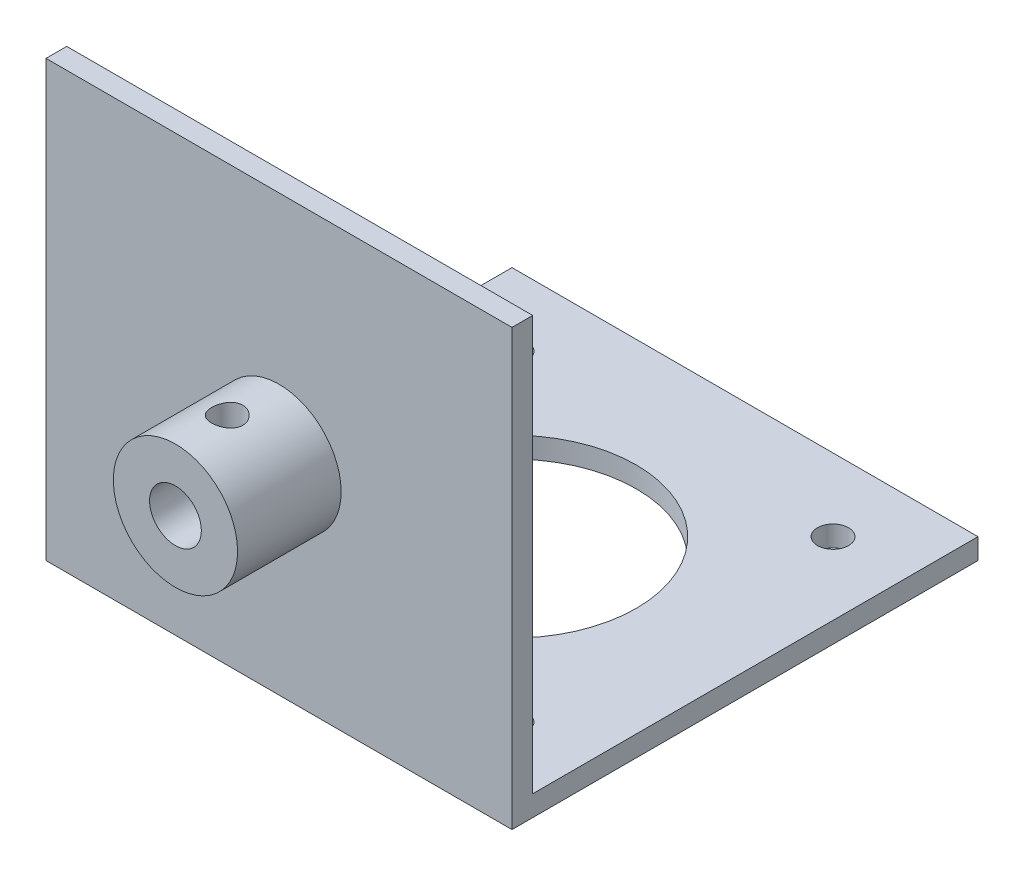
SolidWorks part; units mm, degrees
material "5052-H36"
ref_plane "前视基准面" through (0, 0, 0) normal (0, 0, 1) x (1, 0, 0)
ref_plane "上视基准面" through (0, 0, 0) normal (0, 1, 0) x (1, 0, 0)
ref_plane "右视基准面" through (0, 0, 0) normal (1, 0, 0) x (0, 0, -1)
sketch "草图1" plane through (0, 0, 0) normal (0, 1, 0) x (1, 0, 0)
  line L13 (0, 0) -> (45, 0)
  line L14 (0, 0) -> (0, 45)
  line L15 (0, 45) -> (45, 45)
  line L16 (45, 0) -> (45, 45)
extrude "凸台-拉伸1" add sketch "草图1" along normal blind 2
sketch "草图3" plane through (0, 2, 0) normal (0, 1, 0) x (1, 0, 0)
  line L0 (0, 45) -> (22.5, 45)
  line L1 (22.5, 45) -> (22.5, 22.5)
  line L3 (22.5, 22.5) -> (38, 22.5)
  line L4 (38, 22.5) -> (38, 38)
  line L5 (38, 38) -> (7, 38)
  line L6 (7, 38) -> (7, 7)
  line L7 (7, 7) -> (38, 7)
  circle A0 centre (22.5, 22.5) radius 12
  circle A1 centre (38, 38) radius 1.5
  circle A2 centre (7, 38) radius 1.5
  circle A3 centre (7, 7) radius 1.5
  circle A4 centre (38, 7) radius 1.5
extrude "切除-拉伸1" cut sketch "草图3" against normal blind 10 contours A2 | A1 | A4 | A3 | A0
sketch "草图7" plane through (0, 2, 0) normal (0, 1, 0) x (1, 0, 0)
  line L0 (0, 0) -> (0, 2)
  line L1 (0, 0) -> (0, 45) construction
  line L2 (0, 2) -> (45, 2)
  line L3 (45, 0) -> (45, 45) construction
  line L4 (45, 2) -> (45, 0)
  line L5 (45, 0) -> (0, 0)
extrude "凸台-拉伸3" add sketch "草图7" along normal blind 40
sketch "草图8" plane through (0, 0, 0) normal (0, 0, 1) x (1, 0, 0)
  line L0 (22.5, 0) -> (22.5, 20)
  line L1 (0, 0) -> (45, 0) construction
  circle A0 centre (22.5, 20) radius 2.5
  circle A1 centre (22.5, 20) radius 6
extrude "凸台-拉伸4" add sketch "草图8" along normal blind 10
sketch "草图9" plane through (0, 0, 0) normal (0, 1, 0) x (1, 0, 0)
  line L0 (22.5, 0) -> (22.5, -5)
  line L1 (16.5, 0) -> (28.5, 0) construction
  circle A0 centre (22.5, -5) radius 1.5
extrude "切除-拉伸2" cut sketch "草图9" against normal through all and the other way through all contours A0
